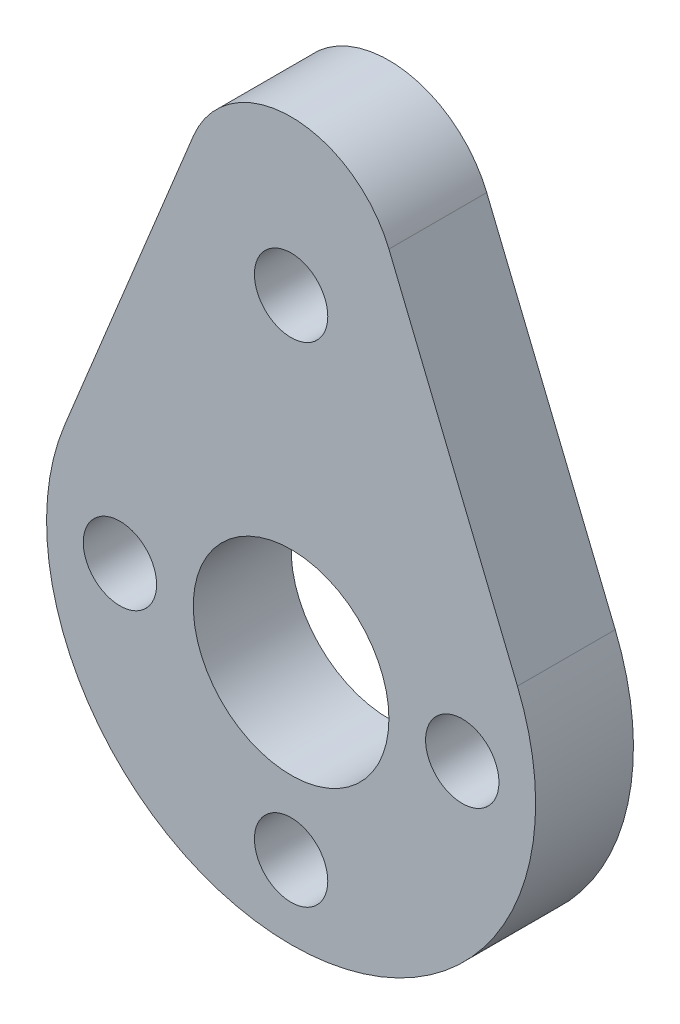
SolidWorks part; units mm, degrees
material "普通碳钢"
ref_plane "前视" through (0, 0, 0) normal (0, 0, 1) x (1, 0, 0)
ref_plane "上视" through (0, 0, 0) normal (0, 1, 0) x (1, 0, 0)
ref_plane "右视" through (0, 0, 0) normal (1, 0, 0) x (0, 0, -1)
sketch "草图1" plane through (0, 0, 0) normal (0, 0, 1) x (1, 0, 0)
  line L0 (-4, 16.636) -> (-9.2558, 3.7856)
  line L1 (4, 16.636) -> (9.2558, 3.7856)
  line L2 (0, 13) -> (0, -10) construction
  arc A0 (-9.2558, 3.7856) -> (9.2558, 3.7856) centre (0, 0) ccw
  arc A1 (-4, 16.636) -> (4, 16.636) centre (0, 15) cw
  circle A2 centre (0, 0) radius 7 construction
  circle A3 centre (-7, 0) radius 1.5
  circle A4 centre (7, 0) radius 1.5
  circle A5 centre (0, -7) radius 1.5
  circle A6 centre (0, 13) radius 1.5
  circle A7 centre (0, 0) radius 10 construction
  circle A8 centre (0, 0) radius 4
  dimension "D1" = 20
  dimension "D3" = 14
  dimension "D4" = 3
  dimension "D6" = 3
  dimension "D8" = 8
  dimension "D2" = 8
  dimension "D5" = 15
  dimension "D7" = 13
extrude "凸台-拉伸1" add sketch "草图1" along normal blind 4
sketch "草图2" plane through (0, 0, 4) normal (0, 0, 1) x (1, 0, 0)
  line L0 (0, 19.3216) -> (0, -10)
  arc A0 (4, 16.636) -> (-4, 16.636) centre (0, 15) ccw construction
  arc A1 (-9.2558, 3.7856) -> (9.2558, 3.7856) centre (0, 0) ccw construction
